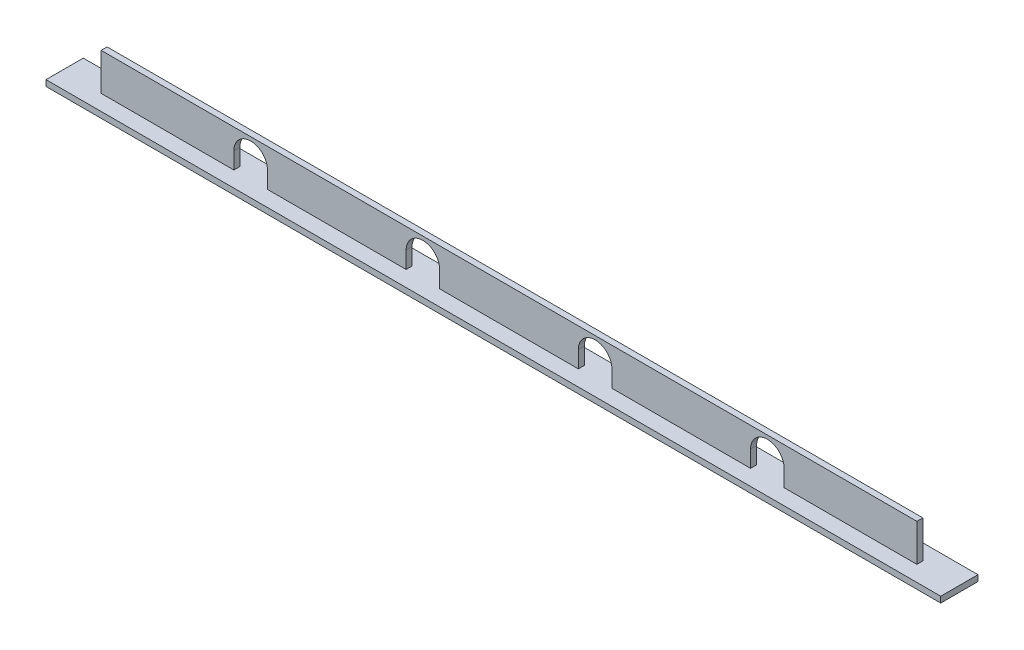
SolidWorks part; units mm, degrees
material "12Х18Н10Т ГОСТ 4543-71"
ref_plane "Спереди" through (0, 0, 0) normal (0, 0, 1) x (1, 0, 0)
ref_plane "Сверху" through (0, 0, 0) normal (0, 1, 0) x (1, 0, 0)
ref_plane "Справа" through (0, 0, 0) normal (1, 0, 0) x (0, 0, -1)
sketch "Эскиз1" plane through (0, 0, 0) normal (0, 0, 1) x (1, 0, 0)
  line L0 (-600, -2.5) -> (-600, -25)
  line L1 (-605, -25) -> (-600, -25)
  line L2 (-605, -25) -> (-605, 25)
  line L3 (-605, 25) -> (605, 25)
  line L4 (605, -25) -> (605, 25)
  line L5 (0, 25) -> (0, -25) construction
  line L6 (-605, 0) -> (605, 0) construction
  line L7 (-555, -2.5) -> (-555, -25)
  line L8 (-555, -25) -> (-369, -25)
  line L9 (-369, -2.5) -> (-369, -25)
  line L10 (-324, -2.5) -> (-324, -25)
  line L11 (-138, -2.5) -> (-138, -25)
  line L12 (-93, -2.5) -> (-93, -25)
  line L13 (93, -2.5) -> (93, -25)
  line L14 (138, -2.5) -> (138, -25)
  line L15 (324, -2.5) -> (324, -25)
  line L16 (369, -2.5) -> (369, -25)
  line L17 (555, -2.5) -> (555, -25)
  line L18 (600, -2.5) -> (600, -25)
  line L19 (-324, -25) -> (-138, -25)
  line L20 (-93, -25) -> (93, -25)
  line L21 (138, -25) -> (324, -25)
  line L22 (369, -25) -> (555, -25)
  line L23 (600, -25) -> (605, -25)
  arc A0 (-555, -2.5) -> (-600, -2.5) centre (-577.5, -2.5) ccw
  arc A1 (-324, -2.5) -> (-369, -2.5) centre (-346.5, -2.5) ccw
  arc A2 (-93, -2.5) -> (-138, -2.5) centre (-115.5, -2.5) ccw
  arc A3 (138, -2.5) -> (93, -2.5) centre (115.5, -2.5) ccw
  arc A4 (369, -2.5) -> (324, -2.5) centre (346.5, -2.5) ccw
  arc A5 (600, -2.5) -> (555, -2.5) centre (577.5, -2.5) ccw
  point P0 (0, 0)
  dimension "D3" = 45
  dimension "D1" = 1210
  dimension "D2" = 50
  dimension "D5" = 5
  dimension "D4" = 6
extrude "Бобышка-Вытянуть1" add sketch "Эскиз1" along normal mid plane 8
sketch "Эскиз3" plane through (0, 25, 0) normal (0, 1, 0) x (1, 0, 0)
  line L0 (0, -208.2618) -> (0, 258.9795) construction
  line L1 (555, -4) -> (555, 4) construction
  line L4 (605, 4) -> (-605, 4)
  line L5 (-605, 4) -> (-605, -4)
  line L6 (-605, -4) -> (605, -4)
  line L7 (605, -4) -> (605, 4)
  line L8 (547, 4) -> (-547, 4)
  line L9 (-547, 4) -> (-547, -4)
  line L10 (-547, -4) -> (547, -4)
  line L11 (547, -4) -> (547, 4)
  dimension "D2" = 8
  dimension "D1" = 0
extrude "Вырез-Вытянуть1" cut sketch "Эскиз3" against normal through all flip side to cut
sketch "Эскиз2" plane through (0, -25, 0) normal (0, -1, 0) x (1, 0, 0)
  line L1 (-600, -25) -> (600, -25)
  line L2 (-600, -25) -> (-600, 25)
  line L3 (-600, 25) -> (600, 25)
  line L4 (600, -25) -> (600, 25)
  line L5 (0, 25) -> (0, -25) construction
  line L6 (-600, 0) -> (600, 0) construction
  point P0 (0, 0)
  dimension "D1" = 50
  dimension "D2" = 1200
extrude "Бобышка-Вытянуть2" add sketch "Эскиз2" along normal blind 8 separate body
equation "\"расстояние между опорами фермы\"= 49"
equation "\"центр боковых направляющих\"= 1210 / 2"
equation "\"толщина полосы\"= 8"
equation "\"ширина полосы\"= 50"
equation "\"ширина боковой направляющей\"= 100 / 2"
equation "\"расстояние между центрами фиксатора\"= 178 / 2"
equation "\"D2@Эскиз3\"=\"толщина полосы\""
